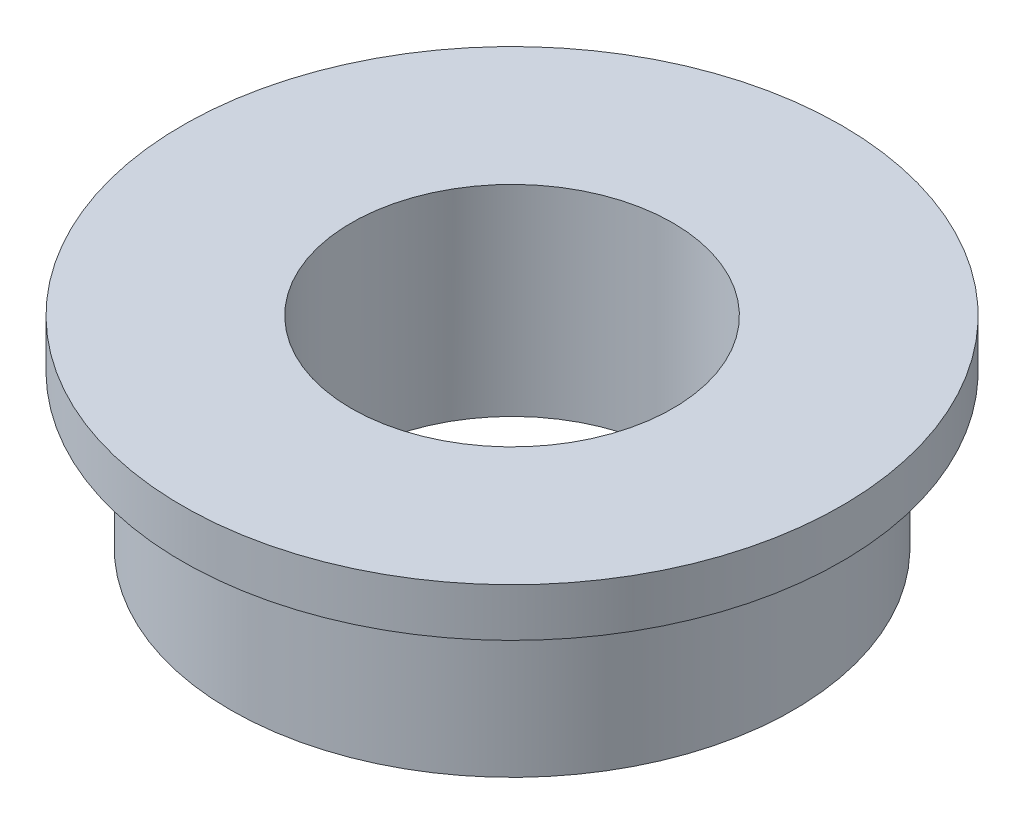
SolidWorks part; units mm, degrees
ref_plane "前视基准面" through (0, 0, 0) normal (0, 0, 1) x (1, 0, 0)
ref_plane "上视基准面" through (0, 0, 0) normal (0, 1, 0) x (1, 0, 0)
ref_plane "右视基准面" through (0, 0, 0) normal (1, 0, 0) x (0, 0, -1)
other "Configuration Table"
sketch "草图2" plane through (0, 0, 0) normal (0, 0, 1) x (1, 0, 0)
  line L0 (0, 0) -> (0, 5.4581) construction
  line L1 (0, 0) -> (3.5, 0)
  line L2 (3.5, 0) -> (3.5, 1.9)
  line L3 (3.5, 1.9) -> (4.1, 1.9)
  line L4 (4.1, 1.9) -> (4.1, 2.5)
  line L5 (4.1, 2.5) -> (0, 2.5)
  line L6 (0, 0) -> (0, 2.5)
  dimension "D1" = 8.2
  dimension "D2" = 7
  dimension "D3" = 0.6
  dimension "D4" = 2.5
revolve "旋转1" add sketch "草图2" angle 360 about L0
sketch "草图3" plane through (0, 0, 0) normal (0, -1, 0) x (1, 0, 0)
  circle A0 centre (0, 0) radius 2
  dimension "D1" = 4
extrude "切除-拉伸1" cut sketch "草图3" against normal up to next
